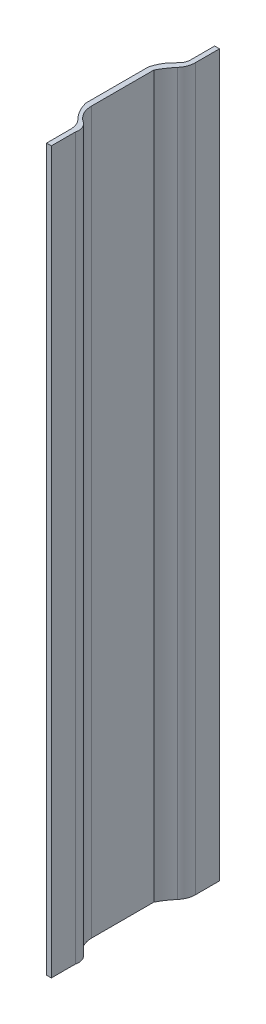
SolidWorks part; units mm, degrees
ref_plane "Front Plane" through (0, 0, 0) normal (0, 0, 1) x (1, 0, 0)
ref_plane "Top Plane" through (0, 0, 0) normal (0, 1, 0) x (1, 0, 0)
ref_plane "Right Plane" through (0, 0, 0) normal (1, 0, 0) x (0, 0, -1)
sketch "Sketch1" plane through (0, 0, 0) normal (0, 1, 0) x (1, 0, 0)
  line L0 (0, 14.6571) -> (0, -15.3429) construction
  line L1 (0, 12.1571) -> (0, 17.1571)
  line L2 (0, -17.8429) -> (0, -12.8429)
  line L3 (0, 17.1571) -> (-1, 17.1571)
  line L4 (0, -17.8429) -> (-1, -17.8429)
  line L5 (-1, -17.8429) -> (-1, -12.8429)
  line L6 (-1, 17.1571) -> (-1, 12.1571)
  line L7 (-3, -6.5) -> (-3, 6.5)
  line L8 (-4.1268, 6.5) -> (-4.1268, -6.5)
  arc A0 (0, 12.1571) -> (-1, 9.4638) centre (-4.1268, 12.1571) cw
  arc A1 (-1, 9.4638) -> (-3, 6.5) centre (10.5619, -0.4948) ccw
  arc A2 (-1, 12.1571) -> (-1.8329, 10.2868) centre (-3.5164, 12.1571) cw
  arc A3 (-1.8329, 10.2868) -> (-4.1268, 6.5) centre (3.2899, 4.5954) ccw
  arc A4 (-3, -6.5) -> (-1, -10.212) centre (1.4447, -6.5) ccw
  arc A5 (-1, -10.212) -> (0, -12.8429) centre (-2.3226, -12.2202) cw
  arc A6 (-1, -12.8429) -> (-2.0871, -10.212) centre (-4.7271, -12.8429) ccw
  arc A7 (-2.0871, -10.212) -> (-4.1268, -6.5) centre (3.318, -4.8254) cw
  point P6 (0, 14.6571)
  point P8 (0, -15.3429)
  point P16 (-3, 0)
  point P30 (0, 0)
  point P31 (0, 0)
  point P32 (0, 0)
  dimension "D1" = 30
  dimension "D2" = 5
  dimension "D3" = 5
  dimension "D4" = 1
  dimension "D5" = 3
  dimension "D6" = 13
extrude "Boss-Extrude1" add sketch "Sketch1" along normal blind 150
